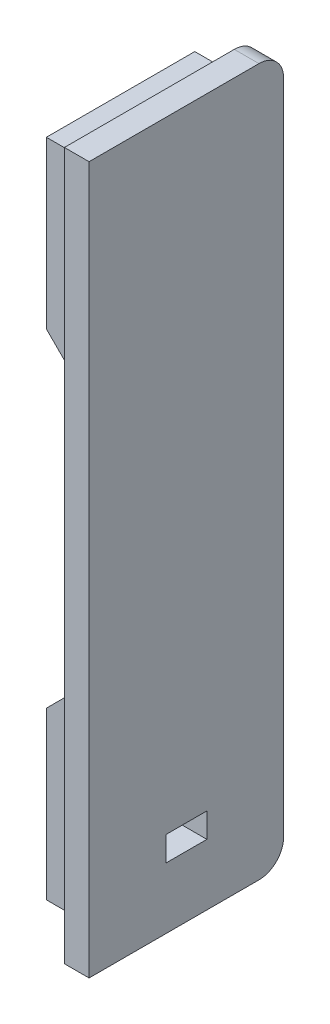
SolidWorks part; units mm, degrees
ref_plane "Front Plane" through (0, 0, 0) normal (0, 0, 1) x (1, 0, 0)
ref_plane "Top Plane" through (0, 0, 0) normal (0, 1, 0) x (1, 0, 0)
ref_plane "Right Plane" through (0, 0, 0) normal (1, 0, 0) x (0, 0, -1)
sketch "Sketch1" plane through (0, 0, 0) normal (1, 0, 0) x (0, 0, -1)
  line L1 (-11.8333, -43) -> (8.8333, -43)
  line L2 (-11.8333, -43) -> (-11.8333, 43)
  line L3 (-11.8333, 43) -> (8.8333, 43)
  line L4 (11.8333, -40) -> (11.8333, 40)
  line L5 (-11.8333, -43) -> (11.8333, 43) construction
  line L6 (-11.8333, 43) -> (11.8333, -43) construction
  arc A0 (11.8333, 40) -> (8.8333, 43) centre (8.8333, 40) ccw
  arc A1 (11.8333, -40) -> (8.8333, -43) centre (8.8333, -40) cw
  point P0 (0, 0)
  dimension "D1" = 3
  dimension "D2" = 3
extrude "Boss-Extrude1" add sketch "Sketch1" along normal blind 3
sketch "Sketch2" plane through (3, 0, 0) normal (1, 0, 0) x (0, 0, -1)
  line L0 (0, 0) -> (0, -60.8438) construction
  line L1 (-2.5, -35.561) -> (2.5, -35.561)
  line L2 (-2.5, -35.561) -> (-2.5, -32.561)
  line L3 (-2.5, -32.561) -> (2.5, -32.561)
  line L4 (2.5, -35.561) -> (2.5, -32.561)
  line L5 (-2.5, -35.561) -> (2.5, -32.561) construction
  line L6 (-2.5, -32.561) -> (2.5, -35.561) construction
  point P0 (0, -34.061)
  point P5 (0, 0)
extrude "Cut-Extrude1" cut sketch "Sketch2" against normal through all
sketch "Sketch3" plane through (0, 0, 0) normal (-1, 0, 0) x (0, 0, 1)
  line L1 (-9.0271, -40.1707) -> (9.0271, -40.1707)
  line L2 (-9.0271, -40.1707) -> (-9.0271, 40.1707)
  line L3 (-9.0271, 40.1707) -> (9.0271, 40.1707)
  line L4 (9.0271, -40.1707) -> (9.0271, 40.1707)
  line L5 (-9.0271, -40.1707) -> (9.0271, 40.1707) construction
  line L6 (-9.0271, 40.1707) -> (9.0271, -40.1707) construction
  point P0 (0, 0)
extrude "Boss-Extrude2" add sketch "Sketch3" along normal blind 5
sketch "Sketch5" plane through (-5, 0, 0) normal (-1, 0, 0) x (0, 0, 1)
  line L1 (-5.9579, -38.0042) -> (5.9579, -38.0042)
  line L2 (-5.9579, -38.0042) -> (-5.9579, 38.0042)
  line L3 (-5.9579, 38.0042) -> (5.9579, 38.0042)
  line L4 (5.9579, -38.0042) -> (5.9579, 38.0042)
  line L5 (-5.9579, -38.0042) -> (5.9579, 38.0042) construction
  line L6 (-5.9579, 38.0042) -> (5.9579, -38.0042) construction
  point P0 (0, 0)
extrude "Cut-Extrude2" cut sketch "Sketch5" against normal blind 5
sketch "Sketch6" plane through (0, 0, 0) normal (0, 0, 1) x (1, 0, 0)
  line L0 (-5, -40.1707) -> (-5, 40.1707) construction
  line L1 (-5, -19.9742) -> (-1.7149, -16.6891)
  line L3 (-5, 19.9742) -> (-1.7149, 16.6891)
  line L4 (-1.7149, -16.6891) -> (-1.7149, 16.6891)
  line L7 (-5, 19.9742) -> (-5, -19.9742)
  point P0 (-5, 0)
  point P2 (-5, 0)
  dimension "D1" = 45
  dimension "D2" = 45
extrude "Cut-Extrude3" cut sketch "Sketch6" against normal through all and the other way through all
sketch "Sketch7" plane through (0, 0, 0) normal (-1, 0, 0) x (0, 0, 1)
  line L1 (-1, -4.5) -> (1, -4.5)
  line L2 (-1, -4.5) -> (-1, 4.5)
  line L3 (-1, 4.5) -> (1, 4.5)
  line L4 (1, -4.5) -> (1, 4.5)
  line L5 (-1, -4.5) -> (1, 4.5) construction
  line L6 (-1, 4.5) -> (1, -4.5) construction
  point P0 (0, 0)
extrude "Boss-Extrude3" add sketch "Sketch7" along normal blind 5
sketch "Sketch8" plane through (0, 0, 1) normal (0, 0, 1) x (1, 0, 0)
  line L4 (0, -4.5) -> (0, 4.5)
  line L5 (0, 4.5) -> (-5, 4.5)
  line L6 (-5, 4.5) -> (-5, -4.5)
  line L7 (-5, -4.5) -> (0, -4.5)
  line L8 (0, -4.5) -> (0, 4.5)
  line L9 (0, 4.5) -> (-5, 4.5)
  line L10 (-5, 4.5) -> (-5, -4.5)
  line L11 (-5, -4.5) -> (0, -4.5)
  circle A0 centre (-2.5106, 0) radius 2.5315
  arc A1 (-5, -3.7487) -> (0, -3.7345) centre (-2.5106, 0) ccw
  arc A2 (0, 3.7345) -> (-5, 3.7487) centre (-2.5106, 0) ccw
  line M5 (0, -4.5) -> (0, 4.5)
  line M6 (0, 4.5) -> (-5, 4.5)
  line M7 (-5, 4.5) -> (-5, -4.5)
  line M8 (-5, -4.5) -> (0, -4.5)
  dimension "D1" = 0
extrude "Cut-Extrude4" cut sketch "Sketch8" against normal blind 5 contours L8 A0 L10 | A1 L10 M8 | A1 L11 M5 | A2 L8 M6 | A2 L9 M7
sketch "Sketch9" plane through (-5, 0, 0) normal (-1, 0, 0) x (0, 0, 1)
  line L1 (-1.2672, -1) -> (1.2672, -1)
  line L2 (-1.2672, -1) -> (-1.2672, 1)
  line L3 (-1.2672, 1) -> (1.2672, 1)
  line L4 (1.2672, -1) -> (1.2672, 1)
  line L5 (-1.2672, -1) -> (1.2672, 1) construction
  line L6 (-1.2672, 1) -> (1.2672, -1) construction
  point P0 (0, 0)
extrude "Cut-Extrude5" cut sketch "Sketch9" against normal blind 1
sketch "Sketch10" plane through (0, 0, 1) normal (0, 0, 1) x (1, 0, 0)
  line L0 (0, 0) -> (-0.2501, 0) construction
  line L1 (0, 0) -> (-7.6994, 0) construction
  line L2 (0.632, -1.1448) -> (-0.193, -4.4539)
  line L3 (-4.4199, -0.7392) -> (-4.336, -0.6668)
  line L4 (-5.0479, -3.258) -> (-4.4199, -0.7392)
  line L8 (-5.0479, 3.258) -> (-4.4199, 0.7392)
  line L9 (-4.4199, 0.7392) -> (-4.336, 0.6668)
  line L10 (0.632, 1.1448) -> (-0.193, 4.4539)
  arc A0 (-0.193, -4.4539) -> (-5.0479, -3.258) centre (-1.7256, -0.2229) cw
  arc A1 (0.632, -1.1448) -> (-4.336, -0.6668) centre (-1.8112, -0.4824) cw
  arc A4 (0.632, 1.1448) -> (-4.336, 0.6668) centre (-1.8112, 0.4824) ccw
  arc A5 (-0.193, 4.4539) -> (-5.0479, 3.258) centre (-1.7256, 0.2229) ccw
  point P5 (-4.336, 0.6668)
sketch "Sketch12" plane through (0, 0, 1) normal (0, 0, 1) x (1, 0, 0)
  line L3 (-4.8362, -1) -> (-5, -1)
  line L4 (-5, -1) -> (-5, -3.7487)
  line L5 (0, -3.7345) -> (0, -0.3242)
  line L6 (-4.8362, -1) -> (-5, -1)
  line L7 (-5, -1) -> (-5, -3.7487)
  line L8 (0, -3.7345) -> (0, -0.3242)
  line L9 (-5, 3.7487) -> (-5, 1)
  line L10 (-5, 1) -> (-4.8362, 1)
  line L11 (0, 0.3242) -> (0, 3.7345)
  line L12 (-5, 3.7487) -> (-5, 1)
  line L13 (-5, 1) -> (-4.8362, 1)
  line L14 (0, 0.3242) -> (0, 3.7345)
  arc A2 (-4.8362, -1) -> (0, -0.3242) centre (-2.5106, 0) ccw
  arc A3 (-4.8362, -1) -> (0, -0.3242) centre (-2.5106, 0) ccw
  arc A6 (-5, -3.7487) -> (0, -3.7345) centre (-2.5106, 0) ccw
  arc A7 (-5, -3.7487) -> (0, -3.7345) centre (-2.5106, 0) ccw
  arc A10 (0, 0.3242) -> (-4.8362, 1) centre (-2.5106, 0) ccw
  arc A11 (0, 0.3242) -> (-4.8362, 1) centre (-2.5106, 0) ccw
  arc A12 (0, 3.7345) -> (-5, 3.7487) centre (-2.5106, 0) ccw
  arc A13 (0, 3.7345) -> (-5, 3.7487) centre (-2.5106, 0) ccw
  dimension "D1" = 0
  dimension "D2" = 0
extrude "Cut-Extrude6" cut sketch "Sketch12" against normal blind 2
extrude "Boss-Extrude5" add sketch "Sketch10" against normal blind 2
sketch "Sketch13" plane through (0, 0, -1) normal (0, 0, -1) x (-1, 0, 0)
  line L0 (0.193, 4.4539) -> (-0.6174, 4.2448)
  line L1 (0.193, -4.4539) -> (-0.7391, -4.0793)
  line L2 (-0.6174, 4.2448) -> (-0.7391, -4.0793)
  line L3 (0, -3.6798) -> (0, 3.6798)
  line L4 (0.193, 4.4539) -> (0, 3.6798)
  line L5 (0, 3.6798) -> (0, 2.251)
  line L6 (4.336, 0.6668) -> (4.4199, 0.7392)
  line L7 (4.4199, 0.7392) -> (5.0479, 3.258)
  line L9 (0, 3.6798) -> (0, 2.251)
  line L10 (4.336, 0.6668) -> (4.4199, 0.7392)
  line L11 (4.4199, 0.7392) -> (5.0479, 3.258)
  line L12 (0, -2.251) -> (0, -3.6798)
  line L13 (0, -3.6798) -> (0.193, -4.4539)
  line L14 (5.0479, -3.258) -> (4.4199, -0.7392)
  line L15 (4.4199, -0.7392) -> (4.336, -0.6668)
  line L16 (0, -2.251) -> (0, -3.6798)
  line L18 (5.0479, -3.258) -> (4.4199, -0.7392)
  line L19 (4.4199, -0.7392) -> (4.336, -0.6668)
  line L21 (0.193, 4.4539) -> (-0.6174, 4.2448)
  line L22 (-0.7391, -4.0793) -> (0.193, -4.4539)
  line L23 (0, -3.6798) -> (0, 3.6798)
  line L25 (0, -3.6798) -> (0, 3.6798)
  line L26 (-0.6174, 4.2448) -> (0.193, 4.4539)
  line L27 (0, 3.6798) -> (0, -3.6798)
  line L28 (0.193, -4.4539) -> (-0.7391, -4.0793)
  line L29 (0.193, 4.4539) -> (0, 3.6798)
  line L30 (0, -3.6798) -> (0.193, -4.4539)
  arc A2 (4.336, 0.6668) -> (0, 2.251) centre (1.8112, 0.4824) ccw
  arc A3 (5.0479, 3.258) -> (0.193, 4.4539) centre (1.7256, 0.2229) ccw
  arc A6 (0.193, -4.4539) -> (5.0479, -3.258) centre (1.7256, -0.2229) ccw
  arc A7 (0, -2.251) -> (4.336, -0.6668) centre (1.8112, -0.4824) ccw
  line M13 (0, -2.251) -> (0, -3.6798)
  line M14 (0, -3.6798) -> (0.193, -4.4539)
  dimension "D1" = 0
  dimension "D2" = 0
extrude "Boss-Extrude6" add sketch "Sketch13" against normal blind 2 contours L29 L0 L2 L1 L3 M14 M13
sketch "Sketch15" plane through (0, 0, -1) normal (0, 0, -1) x (-1, 0, 0)
  line L0 (0, 0) -> (6.6968, 0) construction
  line L1 (5.0479, 3.258) -> (4.0385, 1.6855)
  line L2 (4.0385, 1.6855) -> (4.7339, 1.6855)
  line L3 (4.0385, 1.6855) -> (4.0385, -1.6855)
  line L4 (0.193, 4.4539) -> (0, 4.4041)
  line L5 (0, 4.4041) -> (0, 2.251)
  line L6 (4.336, 0.6668) -> (4.4199, 0.7392)
  line L7 (4.4199, 0.7392) -> (5.0479, 3.258)
  line L8 (0.193, 4.4539) -> (0, 4.4041)
  line L9 (0, 4.4041) -> (0, 2.251)
  line L10 (4.336, 0.6668) -> (4.4199, 0.7392)
  line L11 (4.4199, 0.7392) -> (5.0479, 3.258)
  line L12 (0, -2.251) -> (0, -4.3763)
  line L13 (0, -4.3763) -> (0.193, -4.4539)
  line L14 (5.0479, -3.258) -> (4.4199, -0.7392)
  line L15 (4.4199, -0.7392) -> (4.336, -0.6668)
  line L16 (0, -2.251) -> (0, -4.3763)
  line L17 (0, -4.3763) -> (0.193, -4.4539)
  line L18 (5.0479, -3.258) -> (4.4199, -0.7392)
  line L19 (4.4199, -0.7392) -> (4.336, -0.6668)
  line L20 (4.0385, -1.6855) -> (4.7339, -1.6855)
  line L21 (4.7339, 1.6855) -> (4.7339, -1.6855)
  line L22 (4.0385, 1.6855) -> (4.7339, -1.6855) construction
  line L23 (4.0385, -1.6855) -> (4.7339, 1.6855) construction
  line L24 (5.0479, -3.258) -> (4.0385, -1.6855)
  arc A1 (0, -2.251) -> (4.336, -0.6668) centre (1.8112, -0.4824) ccw construction
  arc A2 (5.0479, 3.258) -> (0.193, 4.4539) centre (1.7256, 0.2229) ccw
  arc A3 (4.336, 0.6668) -> (0, 2.251) centre (1.8112, 0.4824) ccw
  arc A4 (5.0479, 3.258) -> (0.193, 4.4539) centre (1.7256, 0.2229) ccw
  arc A5 (4.336, 0.6668) -> (0, 2.251) centre (1.8112, 0.4824) ccw
  arc A6 (0.193, -4.4539) -> (5.0479, -3.258) centre (1.7256, -0.2229) ccw
  arc A7 (0, -2.251) -> (4.336, -0.6668) centre (1.8112, -0.4824) ccw
  arc A8 (0.193, -4.4539) -> (5.0479, -3.258) centre (1.7256, -0.2229) ccw
  arc A9 (0, -2.251) -> (4.336, -0.6668) centre (1.8112, -0.4824) ccw
  arc A10 (4.336, 0.6668) -> (0, 2.251) centre (1.8112, 0.4824) ccw construction
  point P8 (4.3862, 0)
  arc M21 (0, 2.251) -> (4.336, 0.6668) centre (1.8112, 0.4824) cw
  line M22 (4.336, 0.6668) -> (4.4199, 0.7392)
  line M23 (4.4199, 0.7392) -> (5.0479, 3.258)
  dimension "D1" = 0
  dimension "D2" = 0
extrude "Cut-Extrude7" cut sketch "Sketch15" against normal blind 2 contours L1 L2 M23 | L2 M21 M22 M23 | A9 L20 L18 L19 | L24 L18 L20
